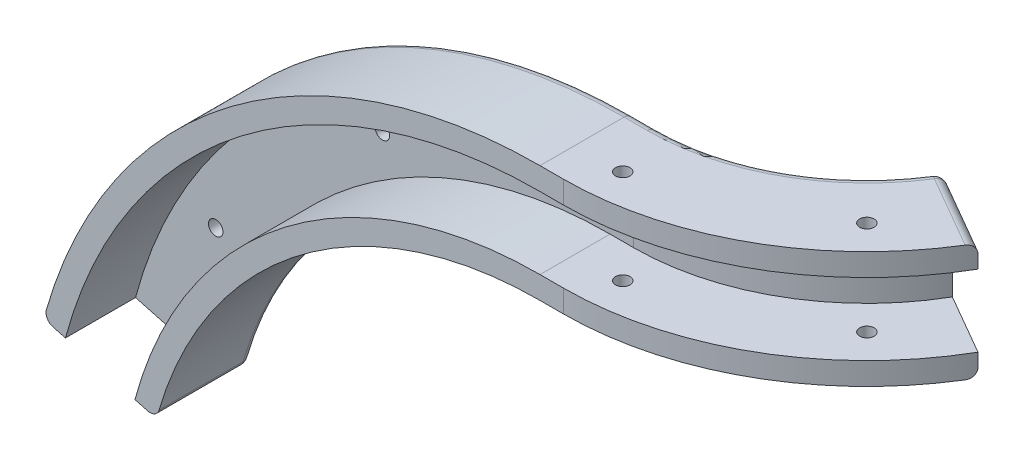
SolidWorks part; units mm, degrees
ref_plane "前视基准面" through (0, 0, 0) normal (0, 0, 1) x (1, 0, 0)
ref_plane "上视基准面" through (0, 0, 0) normal (0, 1, 0) x (1, 0, 0)
ref_plane "右视基准面" through (0, 0, 0) normal (1, 0, 0) x (0, 0, -1)
other "Configuration Table"
sketch "草图1" plane through (0, 0, 0) normal (0, 0, 1) x (1, 0, 0)
  line L0 (0, 0) -> (0, 110) construction
  line L1 (0, 0) -> (-106.2518, 28.4701) construction
  line L2 (-106.2518, 28.4701) -> (-82.1037, 21.9996)
  line L3 (-48.75, 84.4375) -> (0, 0) construction
  line L4 (0, 110) -> (5, 110)
  line L5 (0, 110) -> (0, 85) construction
  line L6 (0, 85) -> (5, 85)
  line L7 (5, 110) -> (5, 85)
  line L8 (-84.4375, 48.75) -> (0, 0) construction
  arc A0 (0, 110) -> (-106.2518, 28.4701) centre (0, 0) ccw
  arc A1 (0, 85) -> (-82.1037, 21.9996) centre (0, 0) ccw
  arc A2 (0, 97.5) -> (-94.1778, 25.2349) centre (0, 0) ccw construction
  circle A3 centre (-48.75, 84.4375) radius 1.55
  circle A5 centre (-84.4375, 48.75) radius 1.55
  dimension "D1" = 85
  dimension "D2" = 110
  dimension "D5" = 97.5
  dimension "D6" = 3.1
  dimension "D7" = 3.1
  dimension "D8" = 30
  dimension "D3" = 75
  dimension "D4" = 5
  dimension "D9" = 60
extrude "凸台-拉伸1" add sketch "草图1" along normal blind 20
sketch "草图3" plane through (0, 85, 0) normal (0, -1, 0) x (1, 0, 0)
  line L0 (5, 20) -> (5, -45) construction
  line L1 (5, -45) -> (61.2917, -12.5) construction
  line L2 (43.9711, -22.5) -> (61.2917, -12.5)
  line L3 (5, 20) -> (5, 0)
  line L4 (10.0115, 12.2812) -> (5, -45) construction
  line L5 (5, -45) -> (45.6586, -4.3414) construction
  arc A0 (5, 20) -> (61.2917, -12.5) centre (5, -45) cw
  arc A1 (5, 0) -> (43.9711, -22.5) centre (5, -45) cw
  arc A2 (5, 12.5) -> (54.7965, -16.25) centre (5, -45) cw construction
  circle A3 centre (10.0115, 12.2812) radius 1.55
  circle A4 centre (45.6586, -4.3414) radius 1.55
  dimension "D1" = 65
  dimension "D2" = 60
  dimension "D3" = 57.5
  dimension "D4" = 3.1
  dimension "D5" = 3.1
  dimension "D6" = 5
  dimension "D7" = 45
extrude "凸台-拉伸2" add sketch "草图3" against normal up to surface (25 mm away) up to face at (2.5, 110, 10)
fillet "圆角1" radius 2 12 edges at (27.5, 110, -6.0289) (2.5, 110, 0) (27.5, 85, -6.0289) (2.5, 85, 0) (-66.9638, 87.2689, 0) (-51.7447, 67.435, 0) (52.6314, 110, -17.5) (52.6314, 85, -17.5) (-106.2518, 28.4701, 10) (-82.1037, 21.9996, 10) (-94.1778, 25.2349, 0) (43.9711, 97.5, -22.5)
sketch "草图4" plane through (0, 0, 20) normal (0, 0, 1) x (1, 0, 0)
  line L0 (-104.3021, 27.9477) -> (-84.0133, 22.5113) construction
  line L1 (0, 110) -> (0, 85) construction
  line L2 (-101.6154, 27.2278) -> (-86.7401, 23.242)
  line L3 (0, 105.2) -> (5, 105.2)
  line L4 (5, 85) -> (5, 110) construction
  line L5 (5, 105.2) -> (5, 89.8)
  line L6 (5, 89.8) -> (0, 89.8)
  arc A0 (0, 105.2) -> (-101.6154, 27.2278) centre (0, 0) ccw
  arc A1 (-86.7401, 23.242) -> (0, 89.8) centre (0, 0) cw
  dimension "D1" = 89.8
  dimension "D2" = 105.2
extrude "切除-拉伸1" cut sketch "草图4" against normal blind 15
sketch "草图5" plane through (0, 105.2, 0) normal (0, -1, 0) x (1, 0, 0)
  line L0 (45.7032, -21.5) -> (61.2917, -12.5) construction
  line L1 (5, -45) -> (5, 20) construction
  line L2 (5, 20) -> (5, 5)
  line L3 (48.3013, -20) -> (61.2917, -12.5)
  line L4 (61.2917, -12.5) -> (45.6663, -21.5213) construction
  arc A0 (5, 20) -> (61.2917, -12.5) centre (5, -45) cw
  arc A1 (48.3013, -20) -> (5, 5) centre (5, -45) ccw
  arc A2 (5, 12.5) -> (54.7965, -16.25) centre (5, -45) cw construction
  dimension "D1" = 50
  dimension "D2" = 57.5
extrude "切除-拉伸2" cut sketch "草图5" along normal up to surface (15.4 mm away) up to face at (2.5, 89.8, 12.5)
